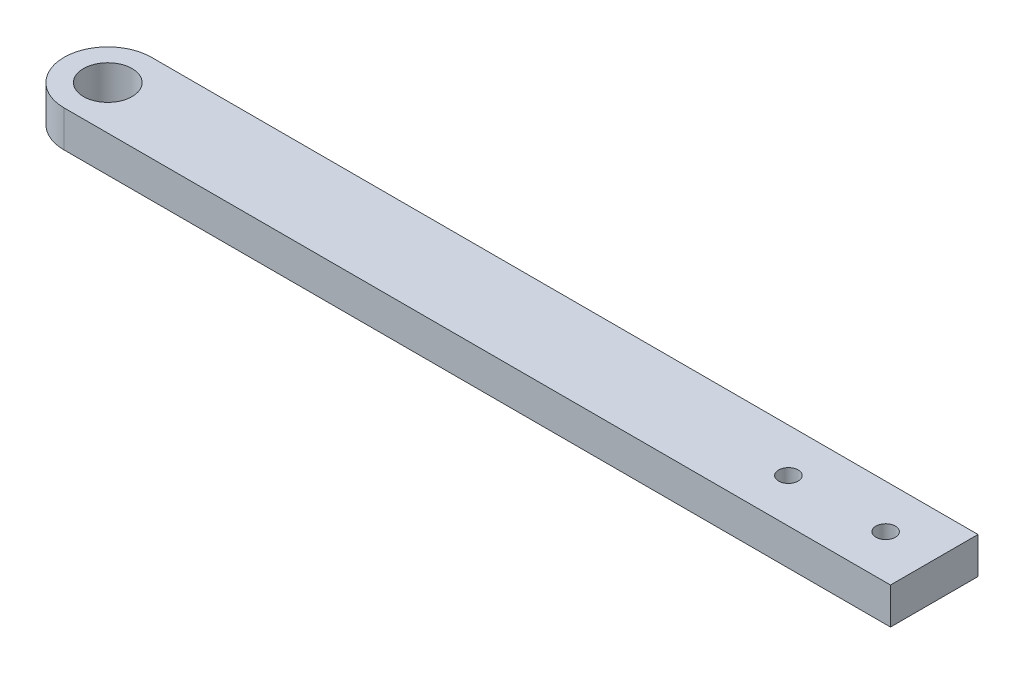
SolidWorks part; units mm, degrees
ref_plane "Front Plane" through (0, 0, 0) normal (0, 0, 1) x (1, 0, 0)
ref_plane "Top Plane" through (0, 0, 0) normal (0, 1, 0) x (1, 0, 0)
ref_plane "Right Plane" through (0, 0, 0) normal (1, 0, 0) x (0, 0, -1)
sketch "Sketch1" plane through (0, 0, 0) normal (0, 1, 0) x (1, 0, 0)
  line L0 (0, 9) -> (170, 9)
  line L1 (170, 9) -> (170, -9)
  line L2 (170, -9) -> (0, -9)
  arc A0 (0, 9) -> (0, -9) centre (0, 0) ccw
  dimension "D1" = 18
  dimension "D2" = 170
  dimension "D3" = 9
extrude "Boss-Extrude1" add sketch "Sketch1" along normal blind 7.5
sketch "Sketch2" plane through (0, 7.5, 0) normal (0, 1, 0) x (1, 0, 0)
  line L0 (170, -9) -> (170, 9) construction
  circle A0 centre (0, 0) radius 5
  circle A1 centre (160, 0) radius 2
  circle A2 centre (140, 0) radius 2
  dimension "D1" = 4
  dimension "D4" = 10
  dimension "D2" = 10
  dimension "D3" = 20
extrude "Cut-Extrude1" cut sketch "Sketch2" against normal through all
